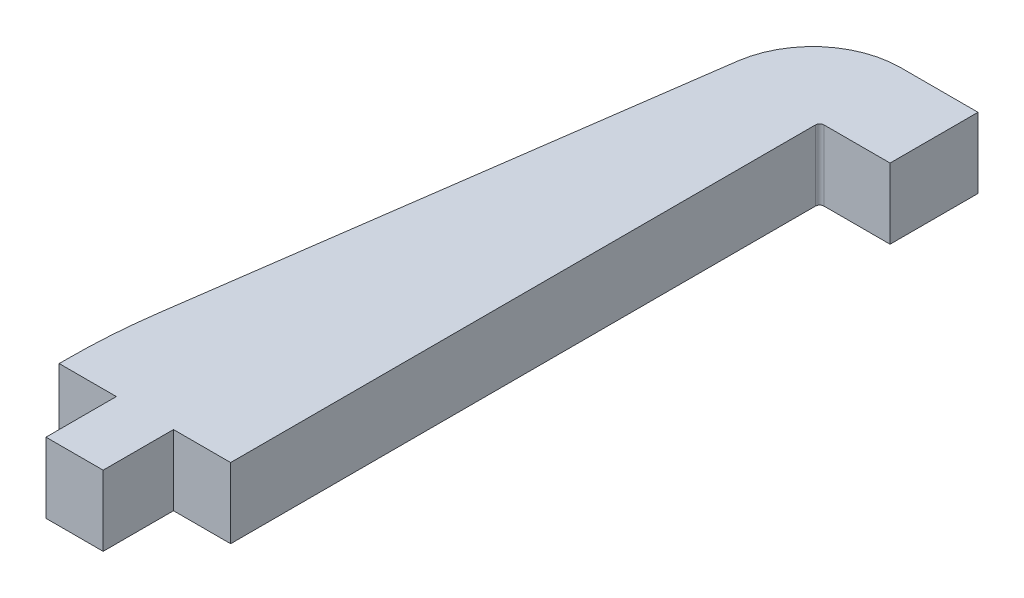
SolidWorks part; units mm, degrees
ref_plane "Front Plane" through (0, 0, 0) normal (0, 0, 1) x (1, 0, 0)
ref_plane "Top Plane" through (0, 0, 0) normal (0, 1, 0) x (1, 0, 0)
ref_plane "Right Plane" through (0, 0, 0) normal (1, 0, 0) x (0, 0, -1)
sketch "Sketch1" plane through (0, 0, 0) normal (0, 1, 0) x (1, 0, 0)
  line L0 (0, 0) -> (19.5, 0)
  line L1 (19.5, 0) -> (19.5, 77)
  line L2 (19.5, 77) -> (0, 77)
  line L3 (0, 77) -> (0, 0)
  line L10 (19.5, 77) -> (19.5, 76.8529)
  line L13 (0, 0) -> (13, 0)
  line L14 (0, 0) -> (0, -8)
  line L15 (0, -8) -> (13, -8)
  line L16 (13, 0) -> (13, -8)
  line L17 (0, -8) -> (6.5, -8)
  line L18 (0, -8) -> (0, 0)
  line L19 (0, 0) -> (6.5, 0)
  line L20 (6.5, -8) -> (6.5, 0)
  line L21 (19.5, 77) -> (27.5, 77)
  line L22 (19.5, 77) -> (19.5, 67)
  line L23 (19.5, 67) -> (27.5, 67)
  line L24 (27.5, 77) -> (27.5, 67)
  dimension "D1" = 19.5
  dimension "D2" = 8
  dimension "D3" = 10
  dimension "D4" = 8
  dimension "D5" = 6.5
  dimension "D6" = 6.5
extrude "Boss-Extrude1" add sketch "Sketch1" along normal blind 8
chamfer "Chamfer1" distance 10 angle 82 1 edges at (0, 4, -77)
fillet "Fillet1" radius 10 1 edges at (10, 4, -77)
fillet "Fillet2" radius 70 1 edges at (0, 4, -5.8463)
fillet "Fillet3" radius 0.5 1 edges at (19.5, 4, -67)
